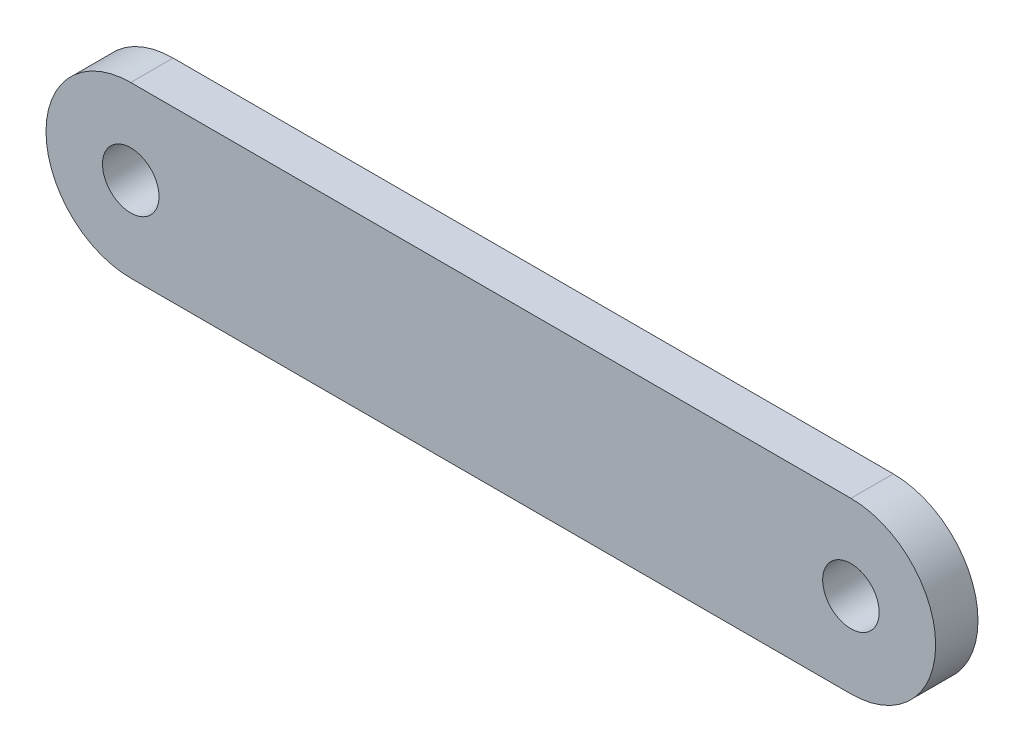
SolidWorks part; units mm, degrees
material "Alliage 1060"
ref_plane "Plan de face" through (0, 0, 0) normal (0, 0, 1) x (1, 0, 0)
ref_plane "Plan de dessus" through (0, 0, 0) normal (0, 1, 0) x (1, 0, 0)
ref_plane "Plan de droite" through (0, 0, 0) normal (1, 0, 0) x (0, 0, -1)
sketch "Esquisse1" plane through (0, 0, 0) normal (0, 0, 1) x (1, 0, 0)
  line L0 (-25.5, 3) -> (0, 3)
  line L1 (0, -3) -> (-25.5, -3)
  arc A0 (0, 3) -> (0, -3) centre (0, 0) cw
  arc A1 (-25.5, -3) -> (-25.5, 3) centre (-25.5, 0) cw
  circle A2 centre (0, 0) radius 1
  circle A3 centre (-25.5, 0) radius 1
  dimension "D1" = 6
  dimension "D3" = 2
  dimension "D2" = 25.5
extrude "Extrusion1" add sketch "Esquisse1" against normal blind 1.5
